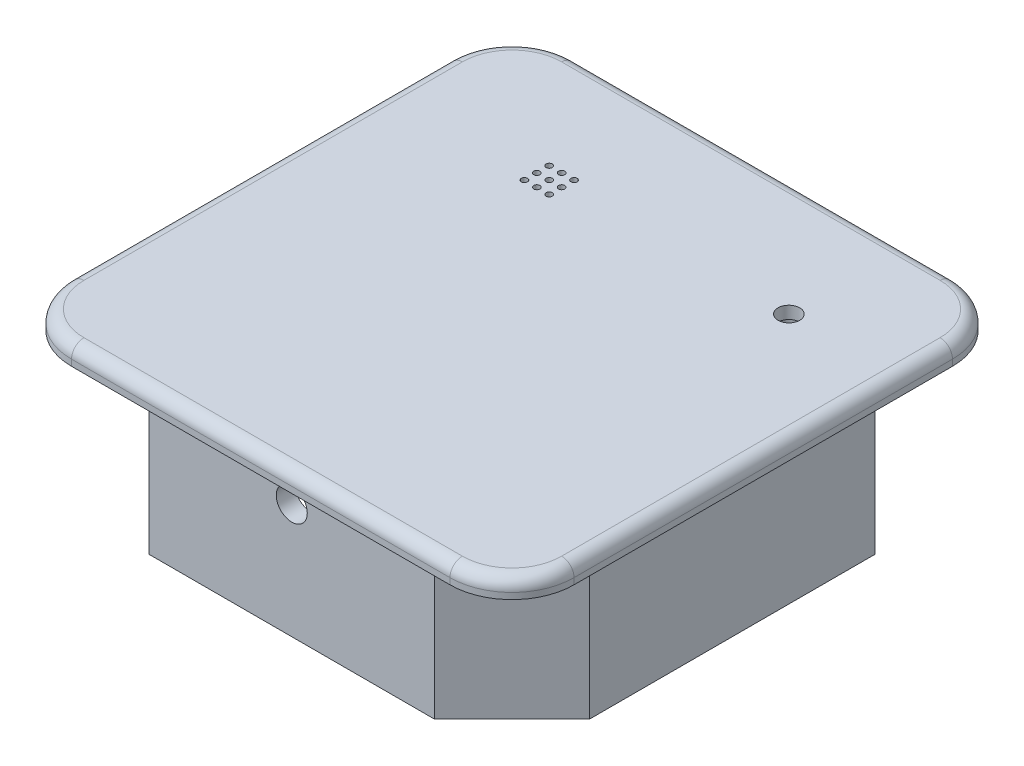
SolidWorks part; units mm, degrees
ref_plane "Front Plane" through (0, 0, 0) normal (0, 0, 1) x (1, 0, 0)
ref_plane "Top Plane" through (0, 0, 0) normal (0, 1, 0) x (1, 0, 0)
ref_plane "Right Plane" through (0, 0, 0) normal (1, 0, 0) x (0, 0, -1)
sketch "Sketch1" plane through (0, 0, 0) normal (0, 1, 0) x (1, 0, 0)
  line L0 (-35.5, 23) -> (-23, 35.5)
  line L1 (-23, -35.5) -> (23, -35.5)
  line L2 (-35.5, -23) -> (-35.5, 23)
  line L3 (-23, 35.5) -> (23, 35.5)
  line L4 (35.5, -23) -> (35.5, 23)
  line L5 (-35.5, -35.5) -> (35.5, 35.5) construction
  line L6 (-35.5, 35.5) -> (35.5, -35.5) construction
  line L7 (23, -35.5) -> (35.5, -23)
  line L8 (-23, -35.5) -> (-35.5, -23)
  line L9 (23, 35.5) -> (35.5, 23)
  point P0 (0, 0)
  dimension "D1" = 71
  dimension "D2" = 71
extrude "Boss-Extrude1" add sketch "Sketch1" along normal mid plane 25
sketch "Sketch2" plane through (0, 0, 0) normal (0, 1, 0) x (1, 0, 0)
  line L0 (35.5, -23) -> (35.5, 23) construction
  line L1 (-30.5, -40.5) -> (30.5, -40.5)
  line L2 (-40.5, -30.5) -> (-40.5, 30.5)
  line L3 (-30.5, 40.5) -> (30.5, 40.5)
  line L4 (40.5, -30.5) -> (40.5, 30.5)
  line L5 (-40.5, -40.5) -> (40.5, 40.5) construction
  line L6 (-40.5, 40.5) -> (40.5, -40.5) construction
  arc A0 (40.5, -30.5) -> (30.5, -40.5) centre (30.5, -30.5) cw
  arc A1 (-30.5, -40.5) -> (-40.5, -30.5) centre (-30.5, -30.5) cw
  arc A2 (40.5, 30.5) -> (30.5, 40.5) centre (30.5, 30.5) ccw
  arc A3 (-30.5, 40.5) -> (-40.5, 30.5) centre (-30.5, 30.5) ccw
  point P0 (0, 0)
  dimension "D2" = 10
  dimension "D1" = 5
extrude "Boss-Extrude2" add sketch "Sketch2" along normal blind 3 from surface at 12.5 starting at face at (0, 12.5, 0)
fillet "Fillet2" radius 2 8 edges at (-40.5, 15.5, 0) (-37.5711, 15.5, -37.5711) (0, 15.5, -40.5) (37.5711, 15.5, -37.5711) (40.5, 15.5, 0) (37.5711, 15.5, 37.5711) (0, 15.5, 40.5) (-37.5711, 15.5, 37.5711)
shell "Shell1" thickness 3
ref_plane "Plane2" through (0, 0, 0) normal (0.7071, 0, 0.7071) x (0.7071, 0, -0.7071)
ref_plane "Plane3" through (0, 0, 0) normal (0.7071, 0, -0.7071) x (-0.7071, 0, -0.7071)
sketch "Sketch6" plane through (0, 0, 0) normal (0.7071, 0, 0.7071) x (0.7071, 0, -0.7071)
  line L0 (0, 0) -> (0, -19.0652) construction
  line L1 (0, -5.5) -> (0, 5.5) construction
sketch "Sketch11" plane through (0, 0, 0) normal (1, 0, 0) x (0, 0, -1)
  line L0 (-32.5, 10.4) -> (-29.5, 10.4)
  line L1 (-29.5, 10.4) -> (-29.5, 8.4)
  line L2 (-29.5, 8.4) -> (-32.5, 8.4)
  line L4 (-32.5, 8.4) -> (-32.5, 10.4)
  line L6 (30.5, 12.5) -> (-30.5, 12.5) construction
  line L7 (-32.5, 12.5) -> (-32.5, -12.5) construction
  dimension "D1" = 2.1
  dimension "D2" = 3
  dimension "D3" = 2
  dimension "D4" = 0
extrude "Boss-Extrude5" add sketch "Sketch11" along normal blind 40 from offset 20 offset against normal yes
sketch "Sketch12" plane through (0, 12.5, 0) normal (0, -1, 0) x (1, 0, 0)
  line L2 (-23, 25) -> (-23, -13)
  line L3 (-23, -13) -> (-29, -13)
  line L4 (-29, 25) -> (-29, -13)
  line L5 (-21.0744, 17.0995) -> (-21.0744, 17.0996) construction
  line L7 (23, 25) -> (23, -13)
  line L8 (23, -13) -> (29, -13)
  line L9 (29, 25) -> (29, -13)
  line L10 (23, 6) -> (-23, 6) construction
  line L14 (21.7574, 32.5) -> (-21.7574, 32.5) construction
  line L15 (-23, 25) -> (-29, 25)
  line L18 (23, 25) -> (29, 25)
  point P9 (0, 6)
  dimension "D1" = 46
  dimension "D2" = 6
  dimension "D3" = 7.5
  dimension "D4" = 38
extrude "Boss-Extrude6" add sketch "Sketch12" along normal blind 3.5
sketch "Sketch13" plane through (0, 0, 0) normal (0, 0, 1) x (1, 0, 0)
  line L1 (-29, 9) -> (-25, 9)
  line L2 (-29, 9) -> (-29, 7)
  line L3 (-29, 7) -> (-25, 7)
  line L4 (-25, 9) -> (-25, 7)
  dimension "D1" = 2
  dimension "D2" = 4
sketch "Sketch14" plane through (0, 0, 0) normal (0, 1, 0) x (1, 0, 0)
  line L16 (-23, 35.5) -> (-35.5, 23)
  line L17 (-35.5, 23) -> (-35.5, -23)
  line L18 (-35.5, -23) -> (-23, -35.5)
  line L19 (-23, -35.5) -> (23, -35.5)
  line L20 (23, -35.5) -> (35.5, -23)
  line L21 (35.5, -23) -> (35.5, 23)
  line L22 (35.5, 23) -> (23, 35.5)
  line L23 (23, 35.5) -> (-23, 35.5)
  line L32 (-22.1716, 33.5) -> (-33.5, 22.1716)
  line L33 (-33.5, 22.1716) -> (-33.5, -22.1716)
  line L34 (-33.5, -22.1716) -> (-22.1716, -33.5)
  line L35 (-22.1716, -33.5) -> (22.1716, -33.5)
  line L36 (22.1716, -33.5) -> (33.5, -22.1716)
  line L37 (33.5, -22.1716) -> (33.5, 22.1716)
  line L38 (33.5, 22.1716) -> (22.1716, 33.5)
  line L39 (22.1716, 33.5) -> (-22.1716, 33.5)
  dimension "D1" = 2
sketch "Sketch16" plane through (0, 9, 0) normal (0, -1, 0) x (1, 0, 0)
  line L0 (-7.9685, 0) -> (7.9164, 0) construction
  line L1 (0, 9.7393) -> (0, -8.4372) construction
  line L2 (29, -13) -> (29, 25) construction
  line L3 (29, 25) -> (23, 25) construction
  circle A0 centre (26, 21) radius 0.85
  circle A1 centre (26, -9) radius 0.85
  circle A2 centre (-26, -9) radius 0.85
  circle A3 centre (-26, 21) radius 0.85
  dimension "D1" = 1.7
  dimension "D2" = 3
  dimension "D3" = 4
  dimension "D4" = 30
extrude "Cut-Extrude5" cut sketch "Sketch16" against normal blind 4
sketch "Sketch17" plane through (0, 12.5, 0) normal (0, -1, 0) x (1, 0, 0)
  circle A0 centre (23.0201, -21.6139) radius 1.75
  dimension "D1" = 3.5
extrude "Cut-Extrude6" cut sketch "Sketch17" against normal up to next
sketch "Sketch18" plane through (0, 12.5, 0) normal (0, -1, 0) x (1, 0, 0)
  circle A0 centre (23.0201, -21.6139) radius 1.98
  dimension "D1" = 3.96
extrude "Cut-Extrude7" cut sketch "Sketch18" against normal blind 1
sketch "Sketch19" plane through (-35.5, 0, 0) normal (-1, 0, 0) x (0, 0, 1)
  line L1 (-10, 3.5) -> (10, 3.5)
  line L2 (-10, 3.5) -> (-10, 8.5)
  line L3 (-10, 8.5) -> (10, 8.5)
  line L4 (10, 3.5) -> (10, 8.5)
  line L5 (-10, 3.5) -> (10, 8.5) construction
  line L6 (-10, 8.5) -> (10, 3.5) construction
  point P0 (0, 6)
  dimension "D1" = 5
  dimension "D2" = 20
  dimension "D3" = 6
extrude "Cut-Extrude8" cut sketch "Sketch19" against normal up to next
sketch "Sketch20" plane through (0, 12.5, 0) normal (0, -1, 0) x (1, 0, 0)
  line L44 (20.5147, 29.5) -> (-20.5147, 29.5)
  line L45 (29.5, 20.5147) -> (20.5147, 29.5)
  line L46 (29.5, -20.5147) -> (29.5, 20.5147)
  line L47 (20.5147, -29.5) -> (29.5, -20.5147)
  line L48 (-20.5147, -29.5) -> (20.5147, -29.5)
  line L49 (-29.5, -20.5147) -> (-20.5147, -29.5)
  line L50 (-29.5, 20.5147) -> (-29.5, -20.5147)
  line L51 (-20.5147, 29.5) -> (-29.5, 20.5147)
  line L52 (20.5147, 29.5) -> (-20.5147, 29.5)
  line L53 (29.5, 20.5147) -> (20.5147, 29.5)
  line L54 (29.5, -20.5147) -> (29.5, 20.5147)
  line L55 (20.5147, -29.5) -> (29.5, -20.5147)
  line L56 (-20.5147, -29.5) -> (20.5147, -29.5)
  line L57 (-29.5, -20.5147) -> (-20.5147, -29.5)
  line L58 (-29.5, 20.5147) -> (-29.5, -20.5147)
  line L59 (-20.5147, 29.5) -> (-29.5, 20.5147)
  dimension "D1" = 3
extrude "Extrude-Thin1" add sketch "Sketch20" against normal blind 8 from surface at 25 thin
sketch "Sketch21" plane through (0, 0, 0) normal (0, 1, 0) x (1, 0, 0)
  line L0 (0, 17.187) -> (0, -14.8433) construction
  line L1 (-12.5517, 0) -> (12.9684, 0) construction
  line L3 (-23, -35.5) -> (23, -35.5) construction
  circle A5 centre (0, -32.5) radius 0.85
  circle A6 centre (0, 32.5) radius 0.85
  dimension "D1" = 1.7
  dimension "D2" = 3
extrude "Cut-Extrude9" cut sketch "Sketch21" along normal blind 4 from surface at -12.5 starting at face at (0, -12.5, 0)
sketch "Sketch22" plane through (0, 12.5, 0) normal (0, -1, 0) x (1, 0, 0)
  line L0 (-18.3992, -21) -> (-9.6143, -21) construction
  line L1 (-17, -23) -> (-11.7125, -23) construction
  circle A0 centre (-17, -23) radius 0.5
  circle A1 centre (-15, -23) radius 0.5
  circle A2 centre (-13, -23) radius 0.5
  circle A3 centre (-15, -21) radius 0.5
  circle A4 centre (-17, -21) radius 0.5
  circle A5 centre (-13, -21) radius 0.5
  circle A9 centre (-13, -19) radius 0.5
  circle A10 centre (-15, -19) radius 0.5
  circle A11 centre (-17, -19) radius 0.5
  dimension "D1" = 1
  dimension "D2" = 2
  dimension "D3" = 1
  dimension "D4" = 2
  dimension "D6" = 15
  dimension "D7" = 0
  dimension "D9" = 1
  dimension "D5" = 2
  dimension "D8" = 21
extrude "Cut-Extrude10" cut sketch "Sketch22" against normal up to next
sketch "Sketch23" plane through (0, 0, -35.5) normal (0, 0, -1) x (-1, 0, 0)
  line L0 (30.5, 12.5) -> (-30.5, 12.5) construction
  circle A0 centre (0, 6) radius 2.5
  dimension "D2" = 5
  dimension "D1" = 6.5
extrude "Cut-Extrude12" cut sketch "Sketch23" against normal up to next
sketch "Sketch24" plane through (0, 0, 35.5) normal (0, 0, 1) x (1, 0, 0)
  line L0 (30.5, 12.5) -> (-30.5, 12.5) construction
  circle A0 centre (0, 6) radius 2.5
  dimension "D1" = 5
  dimension "D2" = 6.5
extrude "Cut-Extrude13" cut sketch "Sketch24" against normal up to surface (6 mm away) up to face at (0, 9.4, 29.5)
sketch "Sketch25" plane through (0, 12.5, 0) normal (0, -1, 0) x (1, 0, 0)
  circle A0 centre (-15, -21) radius 6
  circle A1 centre (-15, -21) radius 8
  dimension "D1" = 2
  dimension "D2" = 12
extrude "Boss-Extrude7" add sketch "Sketch25" along normal blind 2
